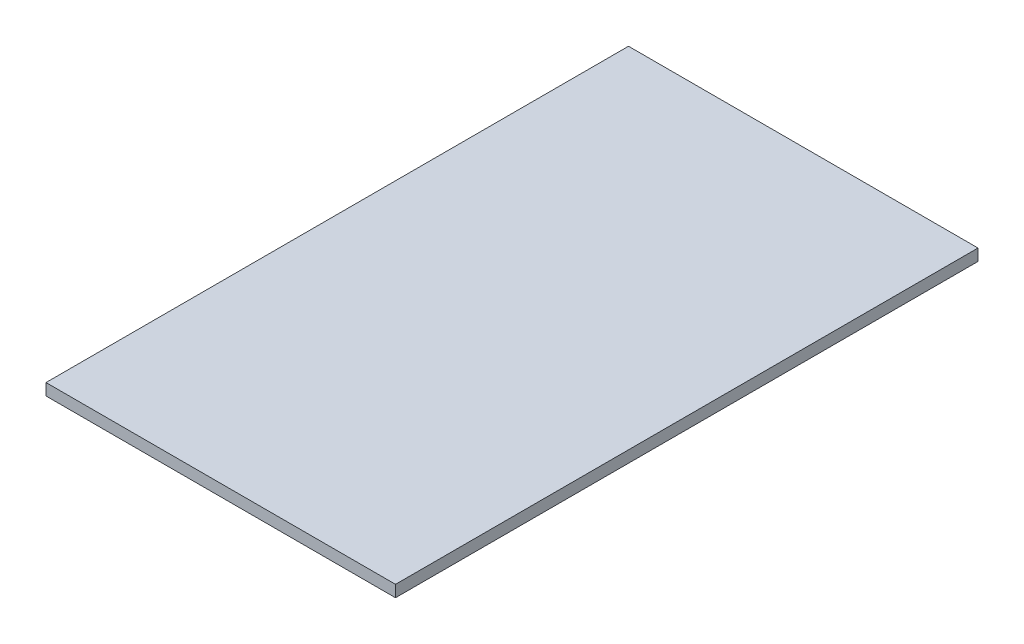
SolidWorks part; units mm, degrees
ref_plane "Front Plane" through (0, 0, 0) normal (0, 0, 1) x (1, 0, 0)
ref_plane "Top Plane" through (0, 0, 0) normal (0, 1, 0) x (1, 0, 0)
ref_plane "Right Plane" through (0, 0, 0) normal (1, 0, 0) x (0, 0, -1)
sketch "Sketch1" plane through (0, 0, 0) normal (0, 1, 0) x (1, 0, 0)
  line L1 (-38.1, -63.5) -> (38.1, -63.5)
  line L2 (-38.1, -63.5) -> (-38.1, 63.5)
  line L3 (-38.1, 63.5) -> (38.1, 63.5)
  line L4 (38.1, -63.5) -> (38.1, 63.5)
  line L5 (-38.1, -63.5) -> (38.1, 63.5) construction
  line L6 (-38.1, 63.5) -> (38.1, -63.5) construction
  point P0 (0, 0)
  dimension "D1" = 76.2
  dimension "D2" = 127
extrude "Boss-Extrude1" add sketch "Sketch1" along normal blind 2.54
